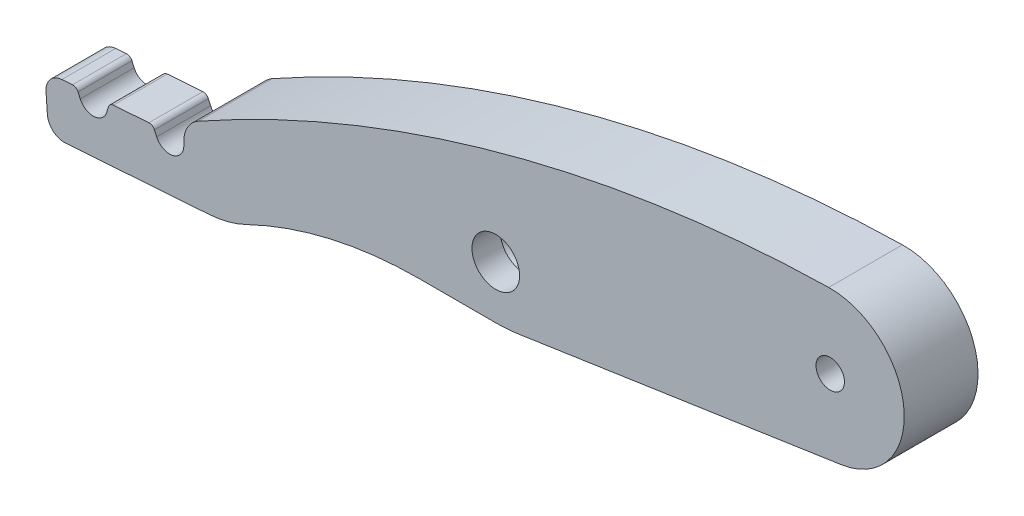
SolidWorks part; units mm, degrees
ref_plane "Front Plane" through (0, 0, 0) normal (0, 0, 1) x (1, 0, 0)
ref_plane "Top Plane" through (0, 0, 0) normal (0, 1, 0) x (1, 0, 0)
ref_plane "Right Plane" through (0, 0, 0) normal (1, 0, 0) x (0, 0, -1)
ref_plane "Plane1" through (0, 0, 47.8) normal (0, 0, 1) x (1, 0, 0)
sketch "Sketch1" plane through (0, 0, 47.8) normal (0, 0, 1) x (1, 0, 0)
  line L0 (-55.0178, 219.948) -> (-50.9969, 212.0565)
  line L1 (-50.9969, 212.0565) -> (-46.8467, 212.3467)
  line L2 (-13.5, 220.8) -> (2.0386, 220.8)
  line L3 (2.0386, 220.8) -> (60.8762, 229.5933)
  line L4 (-54.9894, 223.9164) -> (-54.9894, 220.3238)
  arc A0 (-46.8467, 212.3467) -> (-13.5, 220.8) centre (-13.5, 150.8) cw
  arc A1 (60.8762, 229.5933) -> (58.674, 255.5471) centre (58.9473, 242.5) ccw
  arc A2 (58.674, 255.5471) -> (-54.9894, 223.9164) centre (63.6583, 17.5993) ccw
  arc A3 (-54.9894, 220.3238) -> (-55.0178, 219.948) centre (-57.4894, 220.3238) cw
extrude "Boss-Extrude1" add sketch "Sketch1" against normal blind 3.5
sketch "Sketch2" plane through (0, 0, 44.3) normal (0, 0, -1) x (-1, 0, 0)
  line L0 (60.4463, 220.8187) -> (79.4846, 219.4874)
  line L1 (79.4846, 219.4874) -> (78.8289, 210.1103)
  line L2 (78.8289, 210.1103) -> (46.8467, 212.3467)
  line L3 (13.5, 220.8) -> (-2.0386, 220.8)
  line L4 (-2.0386, 220.8) -> (-60.8762, 229.5933)
  line L5 (54.9894, 223.9164) -> (54.9894, 220.3238)
  line L6 (59.7732, 219.3069) -> (60.4463, 220.8187)
  arc A0 (46.8467, 212.3467) -> (13.5, 220.8) centre (13.5, 150.8) ccw
  arc A1 (-60.8762, 229.5933) -> (-58.674, 255.5471) centre (-58.9473, 242.5) cw
  arc A2 (-58.674, 255.5471) -> (54.9894, 223.9164) centre (-63.6583, 17.5993) cw
  arc A3 (54.9894, 220.3238) -> (59.7732, 219.3069) centre (57.4894, 220.3238) ccw
extrude "Boss-Extrude2" add sketch "Sketch2" along normal blind 9.5 and the other way up to surface (3.5 mm away) other way up to face at (-16.1208, 225.0666, 47.8)
sketch "Sketch3" plane through (0, 0, 34.8) normal (0, 0, -1) x (-1, 0, 0)
  line L0 (73.9134, 219.877) -> (68.0972, 220.2837)
  line L1 (68.0972, 220.2837) -> (68.5533, 218.693)
  line L2 (73.2404, 218.3652) -> (73.9134, 219.877)
  arc A0 (68.5533, 218.693) -> (73.2404, 218.3652) centre (70.9565, 219.3821) ccw
extrude "Cut-Extrude1" cut sketch "Sketch3" against normal through all
sketch "Sketch4" plane through (0, 0, 34.8) normal (0, 0, -1) x (-1, 0, 0)
  line L0 (7.5, 236.6) -> (-7.5, 236.6)
  line L1 (-7.5, 236.6) -> (-7.5, 223.6)
  line L2 (-7.5, 223.6) -> (7.5, 223.6)
  line L3 (7.5, 223.6) -> (7.5, 236.6)
extrude "Cut-Extrude2" cut sketch "Sketch4" against normal blind 8
hole_wizard "5/16 Clearance Hole1" positions "Sketch8" profile "Sketch7" hole size "5/16" standard "ANSI Inch"
sketch "Sketch8" plane through (0, 0, 47.8) normal (0, 0, 1) x (1, 0, 0)
  point P0 (0, 230.1)
sketch "Sketch7" plane through (0, 230.1, 47.8) normal (1, 0, 0) x (0, -1, 0)
  line L0 (0, 0) -> (0, 13)
  line L1 (0, 13) -> (4.2, 13)
  line L2 (4.2, 13) -> (4.2, 0)
  line L5 (4.2, 0) -> (0, 0)
  line L11 (0, -6.35) -> (0, 107.95) construction
  dimension "Thru Hole Dia." = 8.4
  dimension "Thru Hole Depth" = 13
fillet "Fillet1" radius 1 3 edges at (-73.9134, 219.877, 41.3) (-60.4463, 220.8187, 41.3) (-68.0972, 220.2837, 41.3)
fillet "Fillet2" radius 3 2 edges at (-78.8289, 210.1103, 41.3) (-79.4846, 219.4874, 41.3)
fillet "Fillet3" radius 3.5 4 edges at (-7.5, 223.6, 38.8) (-7.5, 236.6, 38.8) (7.5, 236.6, 38.8) (7.5, 223.6, 38.8)
fillet "Fillet4" radius 5 1 edges at (-54.9894, 223.9164, 41.3)
fillet "Fillet5" radius 18 1 edges at (-46.8467, 212.3467, 41.3)
fillet "Fillet6" radius 27.4328 1 edges at (2.0386, 220.8, 41.3)
sketch "Sketch9" plane through (0, 0, 34.8) normal (0, 0, -1) x (-1, 0, 0)
  circle A0 centre (-58.9473, 242.5) radius 2.51
  arc A1 (-58.674, 255.5471) -> (-60.8762, 229.5933) centre (-58.9473, 242.5) ccw construction
  point P3 (0, 0)
extrude "Cut-Extrude3" cut sketch "Sketch9" against normal through all
sketch "Sketch10" plane through (0, 0, 34.8) normal (0, 0, -1) x (-1, 0, 0)
  line L0 (50.9969, 212.0565) -> (55.0178, 219.948)
  line L1 (55.0178, 219.948) -> (56.6361, 223.1242)
  line L2 (56.6361, 223.1242) -> (80.8621, 221.4302)
  line L3 (80.8621, 221.4302) -> (79.9485, 208.3652)
  line L4 (79.9485, 208.3652) -> (50.4339, 210.429)
  line L5 (50.4339, 210.429) -> (50.9969, 212.0565)
extrude "Cut-Extrude4" cut sketch "Sketch10" against normal blind 3.5
